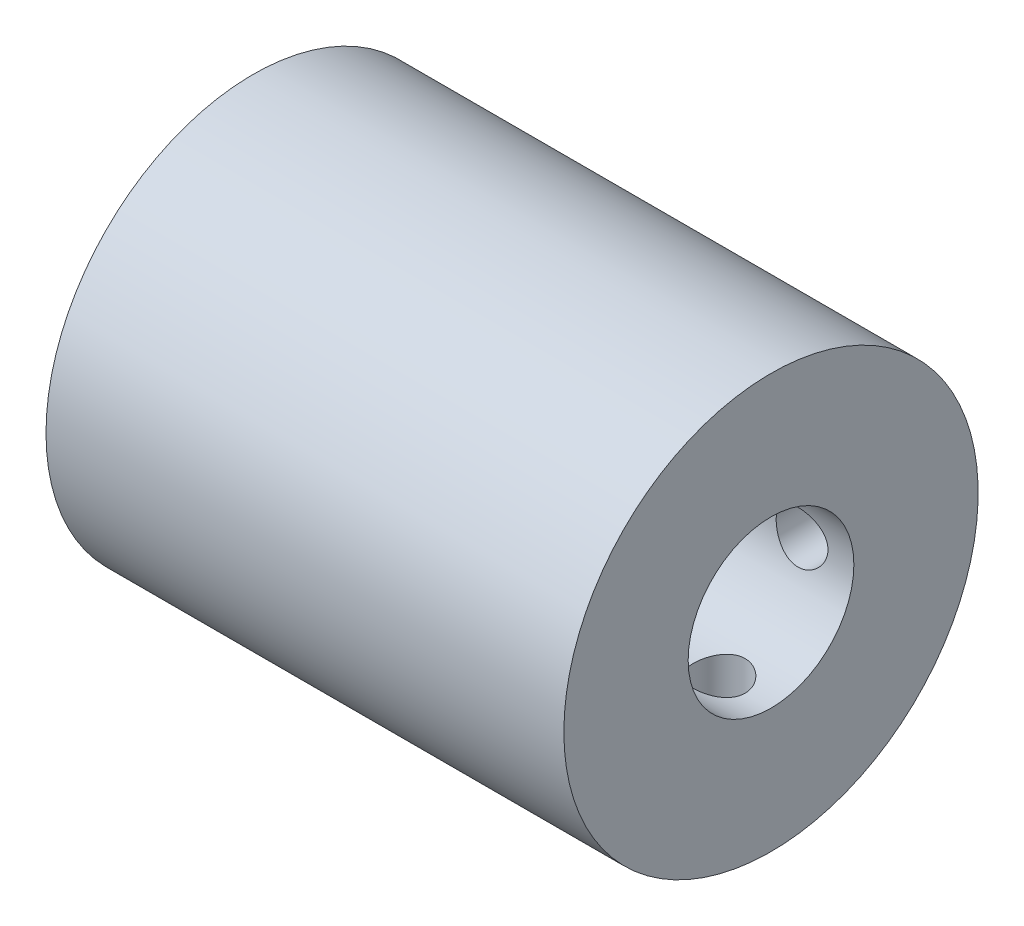
SolidWorks part; units mm, degrees
ref_plane "Front Plane" through (0, 0, 0) normal (0, 0, 1) x (1, 0, 0)
ref_plane "Top Plane" through (0, 0, 0) normal (0, 1, 0) x (1, 0, 0)
ref_plane "Right Plane" through (0, 0, 0) normal (1, 0, 0) x (0, 0, -1)
sketch "Sketch1" plane through (0, 0, 0) normal (0, 0, 1) x (1, 0, 0)
  line L0 (0, 0) -> (25, 0)
  line L1 (0, 0) -> (0, 7.5)
  line L2 (25, 0) -> (25, 6)
  line L3 (0, 7.5) -> (0, 10) construction
  line L4 (0, 10) -> (25, 10) construction
  line L5 (25, 10) -> (25, 6) construction
  line L6 (0, 7.5) -> (12.5, 7.5)
  line L7 (12.5, 7.5) -> (12.5, 6)
  line L8 (12.5, 6) -> (25, 6)
  point P10 (12.5, 0)
  dimension "D1" = 7.5
  dimension "D2" = 6
  dimension "D3" = 25
  dimension "D4" = 10
revolve "Revolve1" add sketch "Sketch1" angle 360 about L4
sketch "Sketch2" plane through (0, 0, 0) normal (0, 0, 1) x (1, 0, 0)
  line L0 (25, 10) -> (12.5, 10) construction
  line L1 (12.5, 10) -> (0, 10) construction
  line L2 (25, 6) -> (25, 14) construction
  circle A0 centre (22.5, 10) radius 1.25
  circle A1 centre (2.5, 10) radius 1.25
  dimension "D1" = 2.5
  dimension "D2" = 20
  dimension "D3" = 2.5
extrude "Cut-Extrude1" cut sketch "Sketch2" against normal blind 10
pattern_circular "CirPattern1" count 2 over 270 about axis through (0, 10, 0) along (-1, 0, 0) of "Cut-Extrude1"
equation "\"D4@Sketch1\"=20/2"
